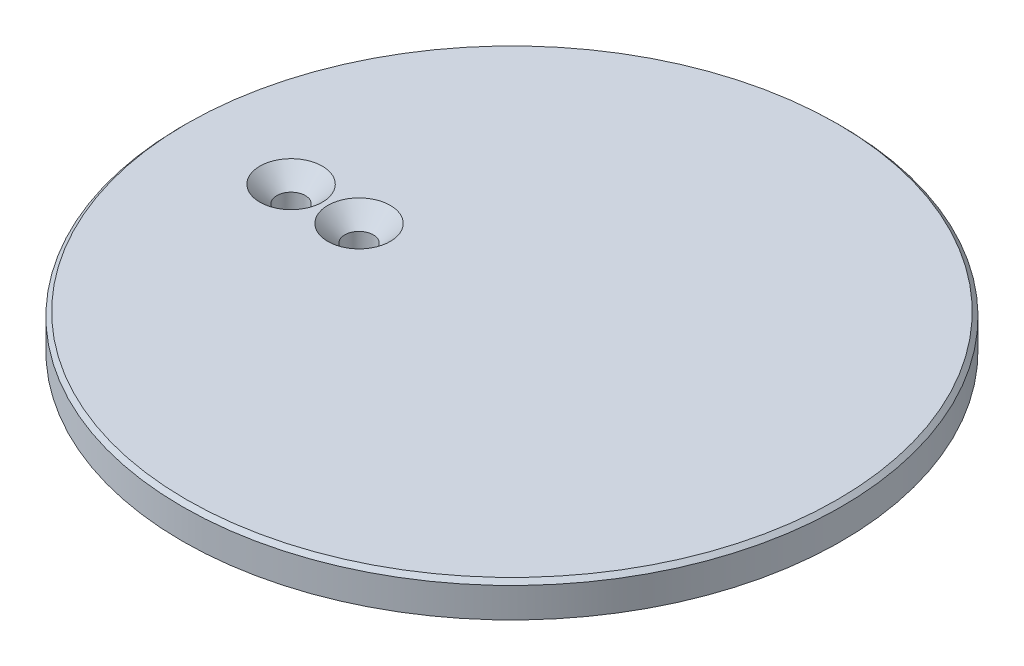
SolidWorks part; units mm, degrees
ref_plane "Ebene vorne" through (0, 0, 0) normal (0, 0, 1) x (1, 0, 0)
ref_plane "Ebene oben" through (0, 0, 0) normal (0, 1, 0) x (1, 0, 0)
ref_plane "Ebene rechts" through (0, 0, 0) normal (1, 0, 0) x (0, 0, -1)
sketch "Skizze1" plane through (0, 0, 0) normal (0, 1, 0) x (1, 0, 0)
  circle A0 centre (0, 0) radius 48.5
  dimension "D1" = 97
extrude "Aufsatz-Linear austragen1" add sketch "Skizze1" along normal blind 5
sketch "Skizze2" plane through (0, 0, 0) normal (0, -1, 0) x (1, 0, 0)
  line L1 (-37.5, 6.5) -> (37.5, 6.5) construction
  line L2 (-37.5, 6.5) -> (-37.5, -6.5) construction
  line L3 (-37.5, -6.5) -> (37.5, -6.5) construction
  line L4 (37.5, 6.5) -> (37.5, -6.5) construction
  line L5 (-37.5, 6.5) -> (37.5, -6.5) construction
  line L6 (-37.5, -6.5) -> (37.5, 6.5) construction
  line L7 (-37.5, 6.5) -> (-17.5, 6.5)
  line L8 (-37.5, 6.5) -> (-37.5, -6.5)
  line L9 (-37.5, -6.5) -> (-17.5, -6.5)
  line L10 (-17.5, 6.5) -> (-17.5, -6.5)
  line L11 (-37.5, 6.5) -> (-17.5, -6.5) construction
  line L12 (-37.5, -6.5) -> (-17.5, 6.5) construction
  point P4 (0, 0)
  point P8 (-27.5, 0)
  dimension "D1" = 75
  dimension "D2" = 13
  dimension "D3" = 20
extrude "Aufsatz-Linear austragen2" add sketch "Skizze2" along normal blind 20
sketch "Skizze3" plane through (0, 0, 0) normal (0, -1, 0) x (1, 0, 0)
  line L0 (-17.5, -6.5) -> (-17.5, 6.5) construction
  line L1 (-37.5, 6.5) -> (-17.5, 6.5)
  line L2 (-37.5, 6.5) -> (-37.5, 8.5)
  line L3 (-37.5, 8.5) -> (-17.5, 8.5)
  line L4 (-17.5, 6.5) -> (-17.5, 8.5)
  line L5 (-37.5, 6.5) -> (-17.5, 8.5) construction
  line L6 (-37.5, 8.5) -> (-17.5, 6.5) construction
  line L7 (-37.5, -6.5) -> (-17.5, -6.5)
  line L8 (-37.5, -6.5) -> (-37.5, -8.5)
  line L9 (-37.5, -8.5) -> (-17.5, -8.5)
  line L10 (-17.5, -6.5) -> (-17.5, -8.5)
  line L11 (-37.5, -6.5) -> (-17.5, -8.5) construction
  line L12 (-37.5, -8.5) -> (-17.5, -6.5) construction
  point P4 (-27.5, 7.5)
  point P10 (-27.5, -7.5)
  dimension "D1" = 2
extrude "Aufsatz-Linear austragen3" add sketch "Skizze3" along normal blind 23
sketch "Skizze4" plane through (0, -20, 0) normal (0, -1, 0) x (1, 0, 0)
  line L0 (-37.5, 0) -> (-17.5, 0) construction
  line L1 (-37.5, 8.5) -> (-37.5, -8.5) construction
  line L2 (-17.5, -8.5) -> (-17.5, 8.5) construction
  circle A0 centre (-32.5, 0) radius 2.1
  circle A1 centre (-22.5, 0) radius 2.1
  dimension "D1" = 4.2
  dimension "D2" = 10
  dimension "D3" = 5
extrude "Schnitt-Linear austragen1" cut sketch "Skizze4" against normal through all
chamfer "Fase4" distance 0.6 angle 45 1 edges at (0, 5, 48.5)
chamfer "Fase6" distance 2.5 angle 45 2 edges at (-22.5, 5, -2.1) (-32.5, 5, -2.1)
